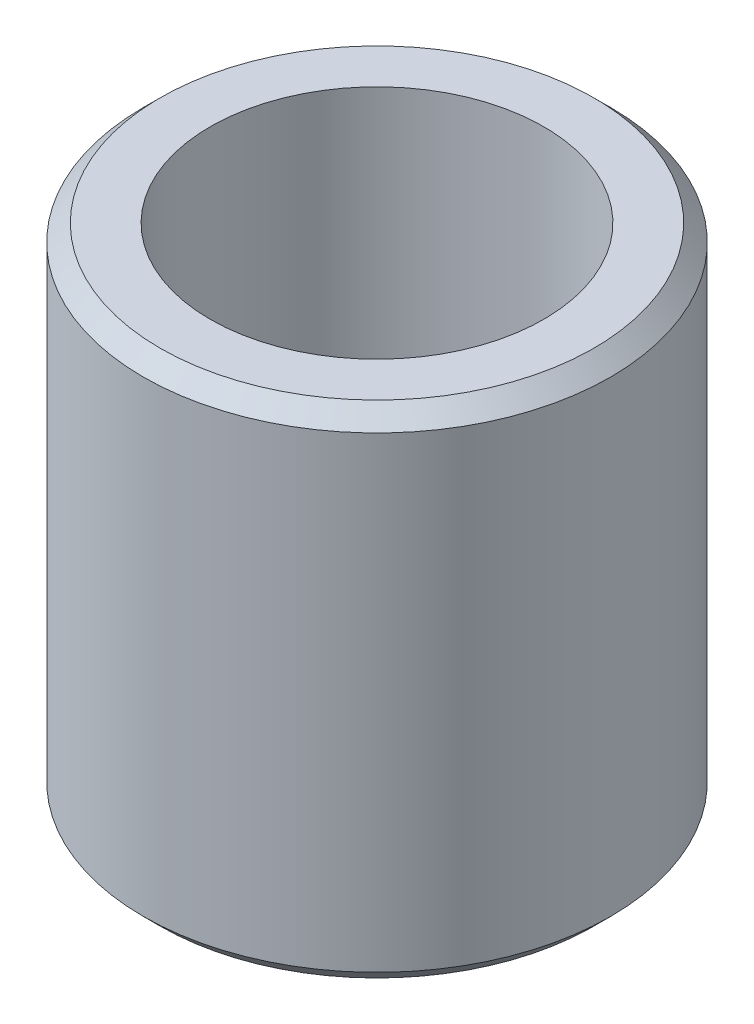
SolidWorks part; units mm, degrees
ref_plane "前视基准面" through (0, 0, 0) normal (0, 0, 1) x (1, 0, 0)
ref_plane "上视基准面" through (0, 0, 0) normal (0, 1, 0) x (1, 0, 0)
ref_plane "右视基准面" through (0, 0, 0) normal (1, 0, 0) x (0, 0, -1)
sketch "草图1" plane through (0, 0, 0) normal (0, 1, 0) x (1, 0, 0)
  circle A0 centre (0, 0) radius 7
  circle A1 centre (0, 0) radius 5
  dimension "D1" = 14
  dimension "D2" = 10
extrude "凸台-拉伸1" add sketch "草图1" along normal mid plane 15
chamfer "倒角1" distance 0.5 angle 45 2 edges at (0, -7.5, 7) (0, 7.5, 7)
